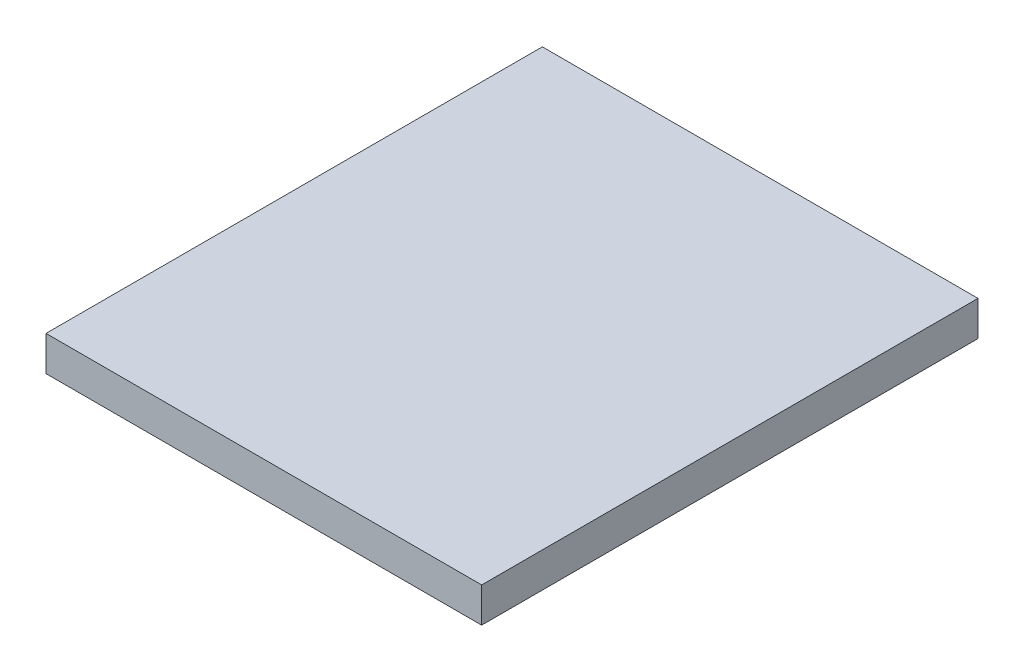
SolidWorks part; units mm, degrees
ref_plane "Front Plane" through (0, 0, 0) normal (0, 0, 1) x (1, 0, 0)
ref_plane "Top Plane" through (0, 0, 0) normal (0, 1, 0) x (1, 0, 0)
ref_plane "Right Plane" through (0, 0, 0) normal (1, 0, 0) x (0, 0, -1)
sketch "Sketch1" plane through (0, 0, 0) normal (0, 1, 0) x (1, 0, 0)
  line L1 (0, 0) -> (100, 0)
  line L2 (0, 0) -> (0, 113.93)
  line L3 (0, 113.93) -> (100, 113.93)
  line L4 (100, 0) -> (100, 113.93)
  dimension "D1" = 113.93
  dimension "D2" = 100
extrude "Boss-Extrude1" add sketch "Sketch1" along normal blind 8
